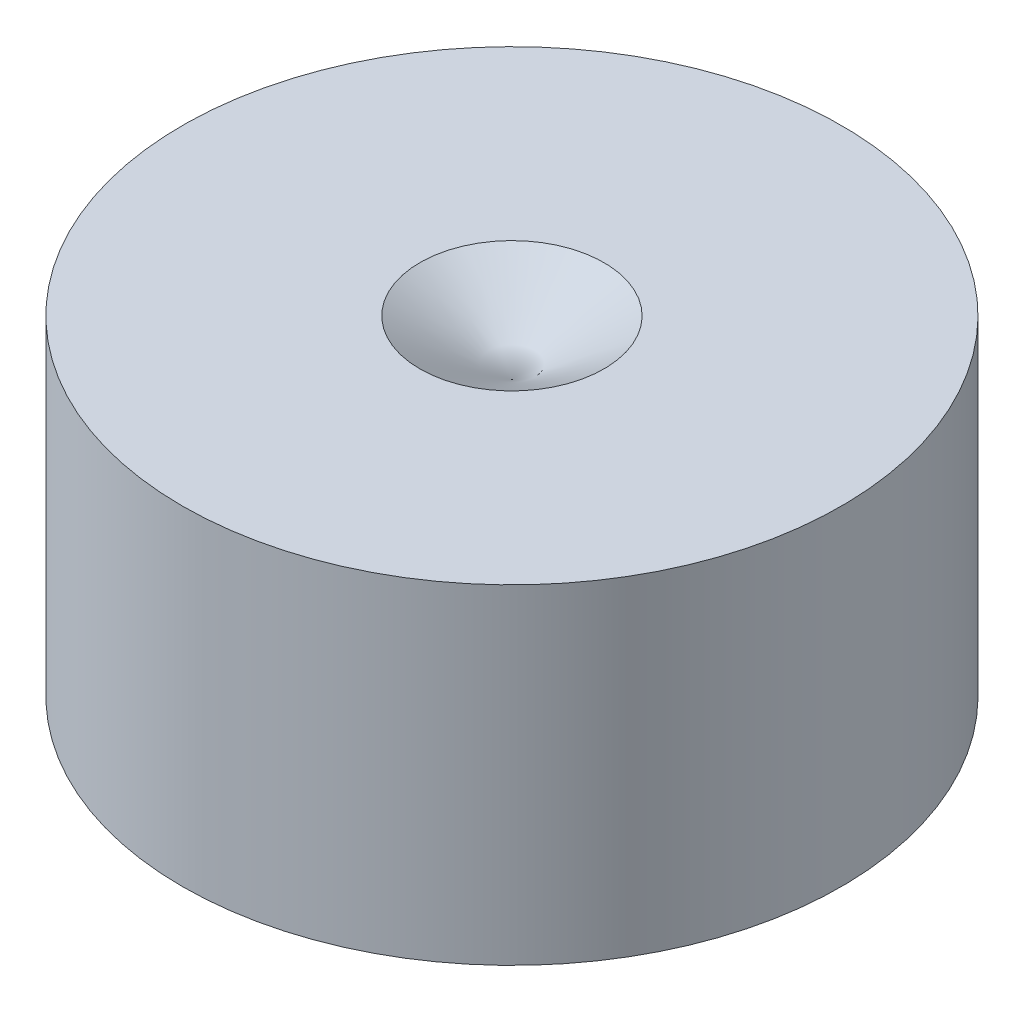
SolidWorks part; units mm, degrees
ref_plane "Plan de face" through (0, 0, 0) normal (0, 0, 1) x (1, 0, 0)
ref_plane "Plan de dessus" through (0, 0, 0) normal (0, 1, 0) x (1, 0, 0)
ref_plane "Plan de droite" through (0, 0, 0) normal (1, 0, 0) x (0, 0, -1)
sketch "Esquisse1" plane through (0, 0, 0) normal (0, 1, 0) x (1, 0, 0)
  circle A0 centre (0, 0) radius 5
extrude "Boss.-Extru.1" add sketch "Esquisse1" along normal blind 5
hole_wizard "Chambrage pour vis à tête ronde bombée #31" positions "Esquisse2" profile "Esquisse3" counterbore size "#3" standard "Ansi Inch"
sketch "Esquisse2" plane through (23.7334, 11, -282) normal (0, 1, 0) x (1, 0, 0)
  line L2 (-23.7334, -130) -> (-23.7334, -309) construction
  line L6 (-23.7334, -130) -> (120.5325, -130) construction
  point P0 (-23.7334, -130)
  point P26 (-23.7334, -282)
  point P29 (87.2666, -130)
  point P31 (87.2666, -282)
sketch "Esquisse3" plane through (0, 11, -152) normal (1, 0, 0) x (0, 0, 1)
  line L0 (0, 0) -> (0, 6.8394)
  line L1 (0, 6.8394) -> (1.397, 6)
  line L2 (1.397, 6) -> (1.397, 1.8034)
  line L3 (1.397, 1.8034) -> (2.7788, 1.8034)
  line L4 (2.7788, 1.8034) -> (2.7788, 0.635)
  line L5 (2.7788, 0.635) -> (3.4138, 0)
  line L6 (3.4138, 0) -> (0, 0)
  line L7 (-2.7788, 0.635) -> (-3.4138, 0) construction
  line L8 (0, 6.8394) -> (-1.397, 6) construction
  line L9 (0, -6.35) -> (0, 107.95) construction
  dimension "Diamètre du perçage" = 2.794
  dimension "Profondeur du perçage" = 6
  dimension "Diamètre du chambrage" = 5.5575
  dimension "Profondeur du chambrage" = 1.8034
  dimension "Diamètre du fraisage entrant" = 6.8275
  dimension "Angle du fraisage entrant" = 90
  dimension "Angle de pointe" = 118
hole_wizard "Chambrage pour vis à tête ronde bombée #32" positions "Esquisse4" profile "Esquisse5" counterbore size "#3" standard "Ansi Inch"
sketch "Esquisse4" plane through (44.2648, 11, 124.5147) normal (0, 1, 0) x (-0.8668, 0, 0.4987)
  line L2 (-23.7334, -130) -> (-23.7334, -309) construction
  line L6 (-23.7334, -130) -> (120.5325, -130) construction
  point P0 (-23.7334, -130)
  point P26 (-23.7334, -282)
  point P29 (87.2666, -130)
  point P31 (87.2666, -282)
sketch "Esquisse5" plane through (0, 11, 0) normal (1, 0, 0) x (0, 0, 1)
  line L0 (0, 0) -> (0, 6.8394)
  line L1 (0, 6.8394) -> (1.397, 6)
  line L2 (1.397, 6) -> (1.397, 1.8034)
  line L3 (1.397, 1.8034) -> (2.7788, 1.8034)
  line L4 (2.7788, 1.8034) -> (2.7788, 0.635)
  line L5 (2.7788, 0.635) -> (3.4138, 0)
  line L6 (3.4138, 0) -> (0, 0)
  line L7 (-2.7788, 0.635) -> (-3.4138, 0) construction
  line L8 (0, 6.8394) -> (-1.397, 6) construction
  line L9 (0, -6.35) -> (0, 107.95) construction
  dimension "Diamètre du perçage" = 2.794
  dimension "Profondeur du perçage" = 6
  dimension "Diamètre du chambrage" = 5.5575
  dimension "Profondeur du chambrage" = 1.8034
  dimension "Diamètre du fraisage entrant" = 6.8275
  dimension "Angle du fraisage entrant" = 90
  dimension "Angle de pointe" = 118
